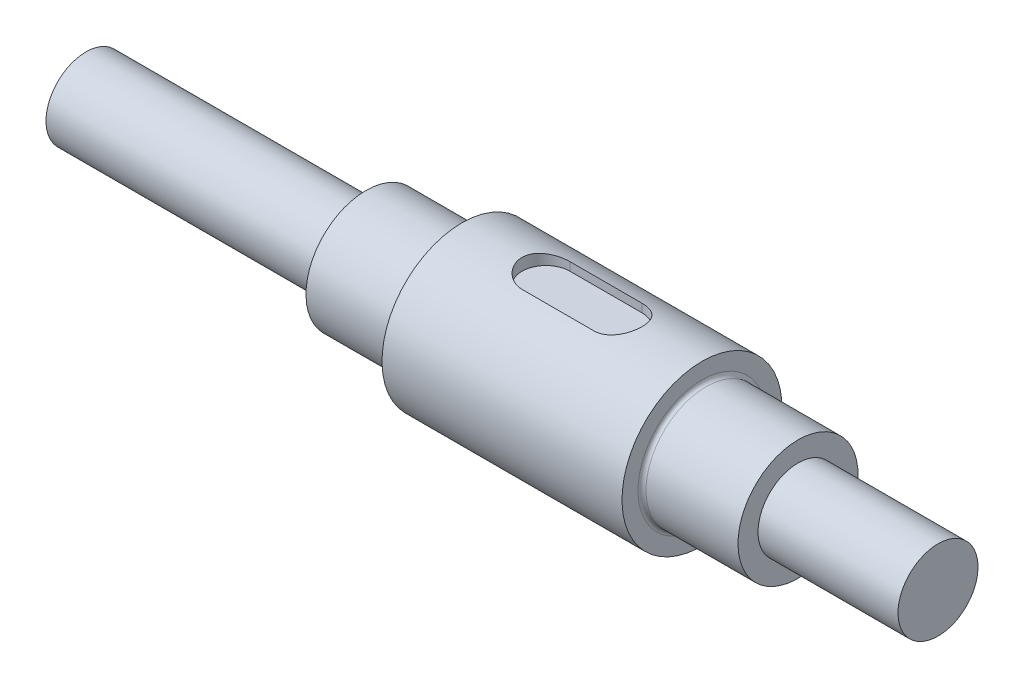
SolidWorks part; units mm, degrees
material "1.7131 (16MnCr5)"
ref_plane "Front Plane" through (0, 0, 0) normal (0, 0, 1) x (1, 0, 0)
ref_plane "Top Plane" through (0, 0, 0) normal (0, 1, 0) x (1, 0, 0)
ref_plane "Right Plane" through (0, 0, 0) normal (1, 0, 0) x (0, 0, -1)
sketch "Sketch1" plane through (0, 0, 0) normal (0, 0, 1) x (1, 0, 0)
  line L0 (-89.4367, 0) -> (89.8745, 0) construction
  line L1 (-60, 43.1339) -> (-60, -35.1585) construction
  line L3 (0, 43.1339) -> (0, -35.1585) construction
  line L4 (-54, 39.7178) -> (-54, -32.6356) construction
  line L5 (-124, 0) -> (-124, 10)
  line L6 (-124, 10) -> (-54, 10)
  line L7 (-54, 10) -> (-54, 15)
  line L8 (-54, 15) -> (-30, 15)
  line L9 (-30, 45.6329) -> (-30, -33.8615) construction
  line L10 (-30, 15) -> (-30, 20)
  line L11 (-30, 20) -> (30, 20)
  line L12 (30, 15) -> (30, 20)
  line L13 (54, 15) -> (30, 15)
  line L14 (54, 10) -> (54, 15)
  line L15 (89, 10) -> (54, 10)
  line L17 (89, 10) -> (89, 0)
  line L18 (89, 0) -> (-124, 0)
  line L19 (60, 61.0896) -> (60, -47.1011) construction
  point P20 (0, 20)
  dimension "D2" = 60
  dimension "D3" = 6
  dimension "D4" = 20
  dimension "D5" = 70
  dimension "D6" = 30
  dimension "D7" = 30
  dimension "D8" = 40
  dimension "D9" = 35
  dimension "D10" = 6
  dimension "D11" = 120
  dimension "D12" = 90
revolve "Revolve2" add sketch "Sketch1" angle 360 about L18
fillet "Fillet1" radius 1 2 edges at (30, 15, 0) (-30, 15, 0)
ref_plane "Plane1" through (0, 20, 0) normal (0, 1, 0) x (1, 0, 0)
sketch "Sketch2" plane through (0, 20, 0) normal (0, 1, 0) x (1, 0, 0)
  line L0 (9, 0) -> (-9, 0) construction
  line L5 (9, -6) -> (-9, -6)
  line L6 (9, 6) -> (-9, 6)
  arc A0 (9, -6) -> (9, 6) centre (9, 0) ccw
  arc A1 (-9, 6) -> (-9, -6) centre (-9, 0) ccw
  point P2 (0, 0)
  dimension "D1" = 30
  dimension "D2" = 12
extrude "Cut-Extrude1" cut sketch "Sketch2" against normal blind 3
